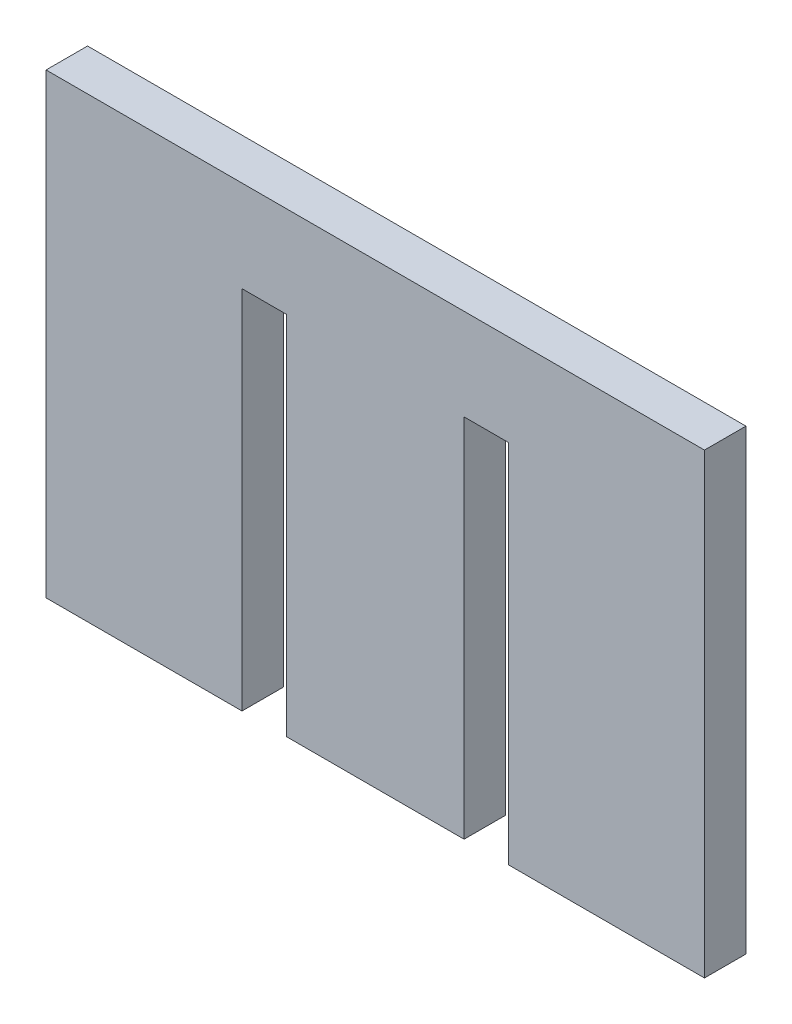
SolidWorks part; units mm, degrees
ref_plane "Front Plane" through (0, 0, 0) normal (0, 0, 1) x (1, 0, 0)
ref_plane "Top Plane" through (0, 0, 0) normal (0, 1, 0) x (1, 0, 0)
ref_plane "Right Plane" through (0, 0, 0) normal (1, 0, 0) x (0, 0, -1)
sketch "Sketch1" plane through (0, 0, 0) normal (0, 0, 1) x (1, 0, 0)
  line L0 (0, 0) -> (0, 35)
  line L1 (0, 35) -> (50.4, 35)
  line L2 (50.4, 35) -> (50.4, 0)
  line L3 (50.4, 0) -> (35.4, 0)
  line L4 (35.4, 0) -> (35.4, 28)
  line L5 (35.4, 28) -> (32, 28)
  line L6 (32, 28) -> (32, 0)
  line L7 (32, 0) -> (18.4, 0)
  line L8 (18.4, 0) -> (18.4, 28)
  line L9 (18.4, 28) -> (15, 28)
  line L10 (15, 28) -> (15, 0)
  line L11 (15, 0) -> (0, 0)
  line L12 (15, 0) -> (18.4, 0) construction
  line L13 (32, 0) -> (35.4, 0) construction
  line L14 (18.4, 28) -> (32, 28) construction
  dimension "D1" = 28
  dimension "D2" = 3.4
  dimension "D3" = 20.4
  dimension "D4" = 15
  dimension "D5" = 35
extrude "Boss-Extrude1" add sketch "Sketch1" along normal blind 3.175
